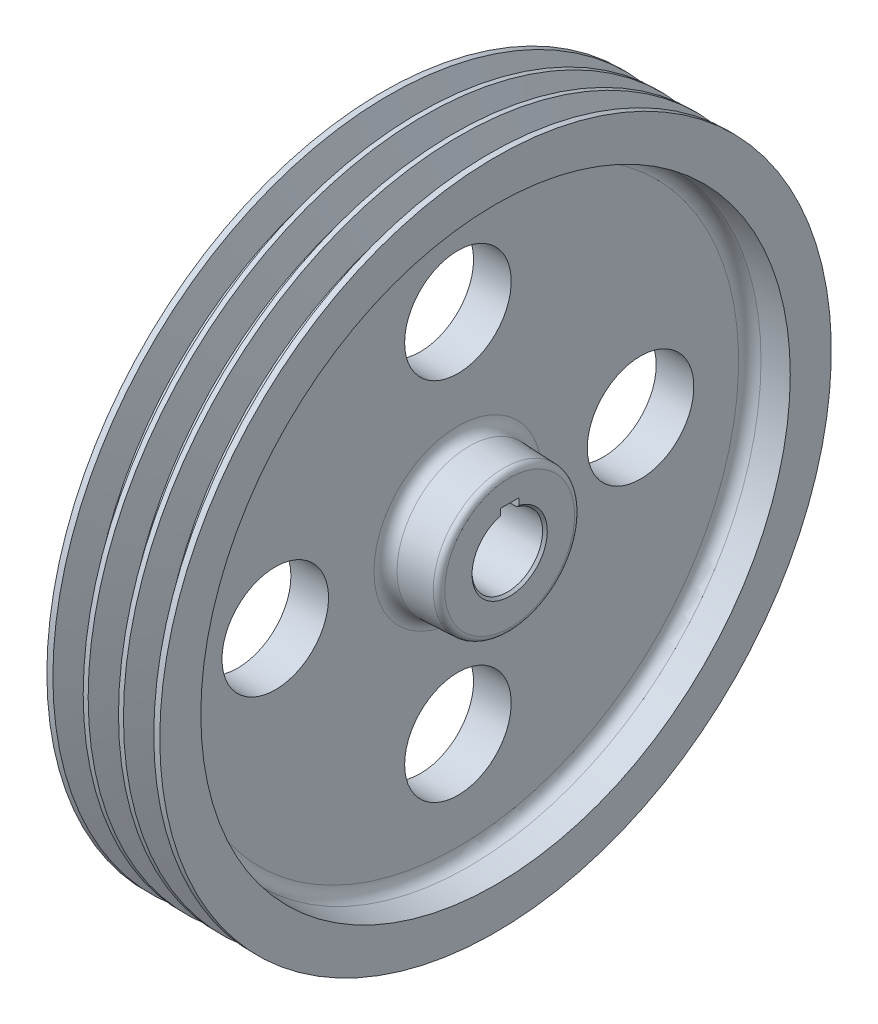
SolidWorks part; units mm, degrees
ref_plane "前视基准面" through (0, 0, 0) normal (0, 0, 1) x (1, 0, 0)
ref_plane "上视基准面" through (0, 0, 0) normal (0, 1, 0) x (1, 0, 0)
ref_plane "右视基准面" through (0, 0, 0) normal (1, 0, 0) x (0, 0, -1)
sketch "草图1" plane through (0, 0, 0) normal (0, 0, 1) x (1, 0, 0)
  line L0 (0, 0) -> (64.8368, 0) construction
  line L1 (-6, 15) -> (-6, 30)
  line L2 (0, 142.75) -> (48, 142.75)
  line L3 (48, 142.75) -> (48, 125.3)
  line L4 (-6, 30) -> (-25, 30) construction
  line L5 (16, 31.9248) -> (16, 124.6602)
  line L6 (54, 15) -> (-6, 15)
  line L7 (2.5531, 142.75) -> (6.4957, 131.3) construction
  line L8 (6.4957, 131.3) -> (11.5043, 131.3) construction
  line L9 (11.5043, 131.3) -> (15.4469, 142.75) construction
  line L10 (0, 140) -> (48, 140) construction
  line L11 (9, 131.3) -> (9, 15) construction
  line L12 (44, 125.3) -> (0, 125.3) construction
  line L13 (48, 125.3) -> (79, 125.3) construction
  line L14 (32, 123.9002) -> (32, 30.8798)
  line L15 (10, 30) -> (54, 30) construction
  line L16 (24, 15) -> (24, 142.75) construction
  line L17 (54, 30) -> (54, 15)
  line L18 (0, 125.3) -> (0, 142.75)
  line L19 (16, 100.3) -> (32, 100.3) construction
  line L20 (16, 55) -> (32, 55) construction
  line L21 (48, 125.3) -> (48, 100.3) construction
  line L22 (48, 100.3) -> (32, 100.3) construction
  line L23 (32, 55) -> (54, 55) construction
  line L24 (54, 55) -> (54, 30) construction
  line L25 (32, 123.9002) -> (48, 125.3)
  line L26 (16, 124.6602) -> (0, 125.3)
  line L27 (16, 31.9248) -> (-6, 30)
  line L28 (32, 30.8798) -> (54, 30)
  point P17 (3.5, 140)
  point P18 (14.5, 140)
  dimension "d2" = 250.6
  dimension "L" = 60
  dimension "B" = 48
  dimension "d" = 30
  dimension "d1" = 60
  dimension "D3" = 5
  dimension "D4" = 2.29
  dimension "dd" = 280
  dimension "f" = 9
  dimension "槽轮角" = 38
  dimension "bd" = 11
  dimension "hf" = 8.7
  dimension "ha" = 2.75
  dimension "da" = 285.5
  dimension "S" = 16
  dimension "S2" = 25
revolve "旋转1" add sketch "草图1" angle 360 about L0
sketch "草图2" plane through (0, 0, 0) normal (0, 0, 1) x (1, 0, 0)
  line L0 (11.5043, 131.3) -> (15.4469, 142.75) construction
  line L1 (6.4957, 131.3) -> (11.5043, 131.3) construction
  line L2 (2.5531, 142.75) -> (6.4957, 131.3) construction
  line L3 (11.5043, 131.3) -> (15.4469, 142.75)
  line L4 (6.4957, 131.3) -> (11.5043, 131.3)
  line L5 (2.5531, 142.75) -> (6.4957, 131.3)
  line L6 (2.5531, 142.75) -> (15.4469, 142.75)
  line L7 (0, 0) -> (123, 0) construction
revolve "切除-旋转1" cut sketch "草图2" angle 360 about L7
pattern_linear "轮槽数" count 3 spacing 15 along (1, 0, 0) of "切除-旋转1"
chamfer "倒角1" distance 1 2 edges at (-6, 0, 15) (54, 0, 15)
sketch "草图4" plane through (-6, 0, 0) normal (-1, 0, 0) x (0, 0, 1)
  line L1 (-4, 14.4568) -> (4, 14.4568)
  line L2 (-4, 14.4568) -> (-4, 18.3)
  line L3 (-4, 18.3) -> (4, 18.3)
  line L4 (4, 14.4568) -> (4, 18.3)
  circle A0 centre (0, 0) radius 15 construction
  point P6 (0.7, 18.3)
  dimension "键槽高度" = 18.3
  dimension "键槽宽度" = 8
  dimension "t1" = 3.3
extrude "切除-拉伸1" cut sketch "草图4" against normal through all
fillet "圆角1" radius 5 4 edges at (32, 0, 123.9002) (16, 0, 31.9248) (16, 0, 124.6602) (32, 0, 30.8798)
fillet "圆角2" radius 2.5 2 edges at (54, 0, 30) (-6, 0, 30)
sketch "草图5" plane through (0, 0, 0) normal (1, 0, 0) x (0, 0, -1)
  line L0 (0, 131.3) -> (0, 15) construction
  circle A0 centre (0, 77.65) radius 22.65
extrude "切除-拉伸2" cut sketch "草图5" along normal through all
pattern_circular "圆孔个数" count 4 over 360 about axis through (0, 0, 0) along (1, 0, 0) of "切除-拉伸2"
